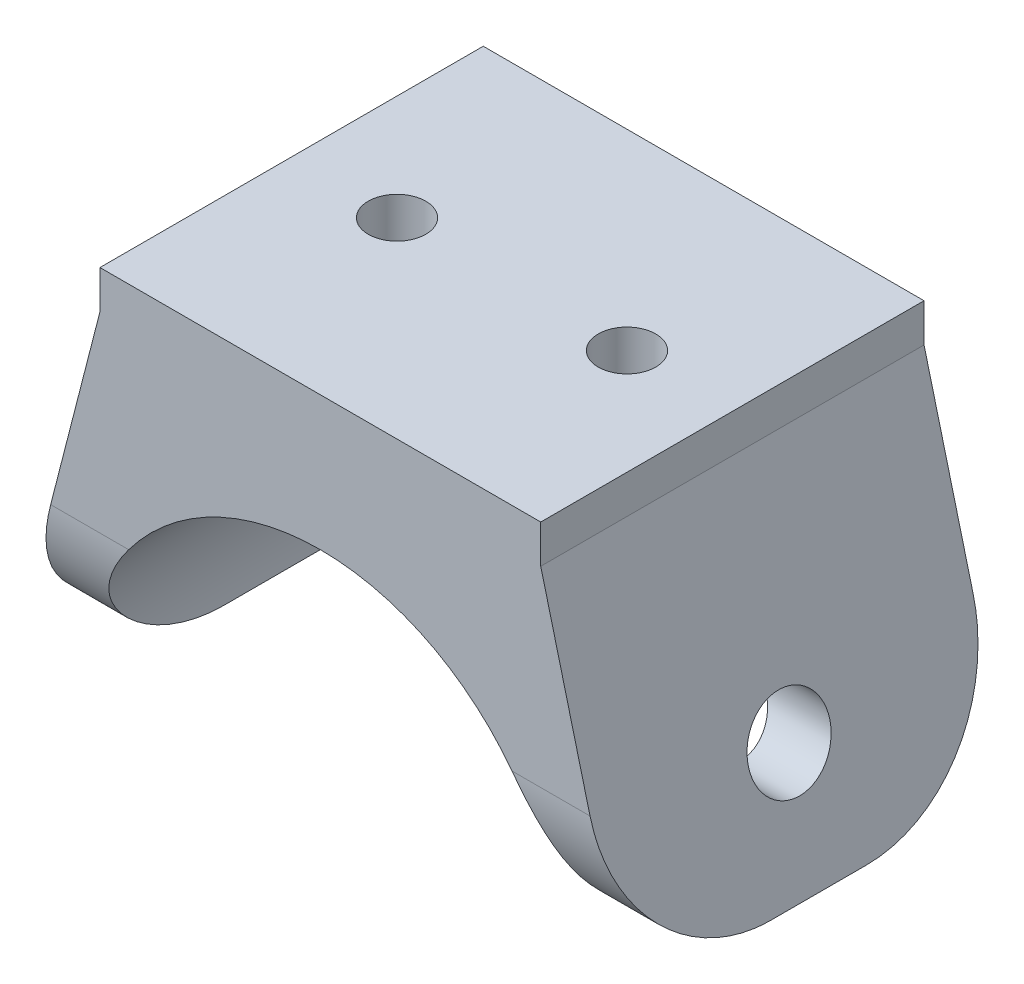
SolidWorks part; units mm, degrees
material "Mahogany"
ref_plane "Front" through (0, 0, 0) normal (0, 0, 1) x (1, 0, 0)
ref_plane "Top" through (0, 0, 0) normal (0, 1, 0) x (1, 0, 0)
ref_plane "Right" through (0, 0, 0) normal (1, 0, 0) x (0, 0, -1)
sketch "Sketch1" plane through (0, 0, 0) normal (0, 0, 1) x (1, 0, 0)
  line L0 (25, 0) -> (32, 0)
  line L1 (32, 0) -> (23, 35)
  line L2 (23, 35) -> (23, 39)
  line L3 (23, 39) -> (-23, 39)
  line L4 (-23, 39) -> (-23, 35)
  line L5 (-23, 35) -> (-32, 0)
  line L6 (-32, 0) -> (-25, 0)
  arc A0 (25, 0) -> (-25, 0) centre (0, 0) ccw
  point P13 (0, 39)
  dimension "D1" = 25
  dimension "D2" = 46
  dimension "D3" = 4
  dimension "D4" = 64
  dimension "D5" = 39
extrude "Boss-Extrude1" add sketch "Sketch1" against normal mid plane 40
sketch "Sketch3" plane through (0, 0, 0) normal (1, 0, 0) x (0, 0, -1)
  line L0 (20, 39) -> (-20, 39) construction
  circle A0 centre (0, 12) radius 4.25
  dimension "D1" = 8.5
  dimension "D2" = 27
extrude "Cut-Extrude1" cut sketch "Sketch3" against normal through all both and the other way through all
sketch "Sketch4" plane through (0, 39, 0) normal (0, 1, 0) x (1, 0, 0)
  circle A0 centre (12, 0) radius 3
  circle A1 centre (-12, 0) radius 3
  dimension "D1" = 6
  dimension "D2" = 24
  dimension "D3" = 12
extrude "Cut-Extrude2" cut sketch "Sketch4" against normal blind 14
fillet "Fillet1" radius 15 4 edges at (-28.5, 0, -20) (28.5, 0, -20) (28.5, 0, 20) (-28.5, 0, 20)
